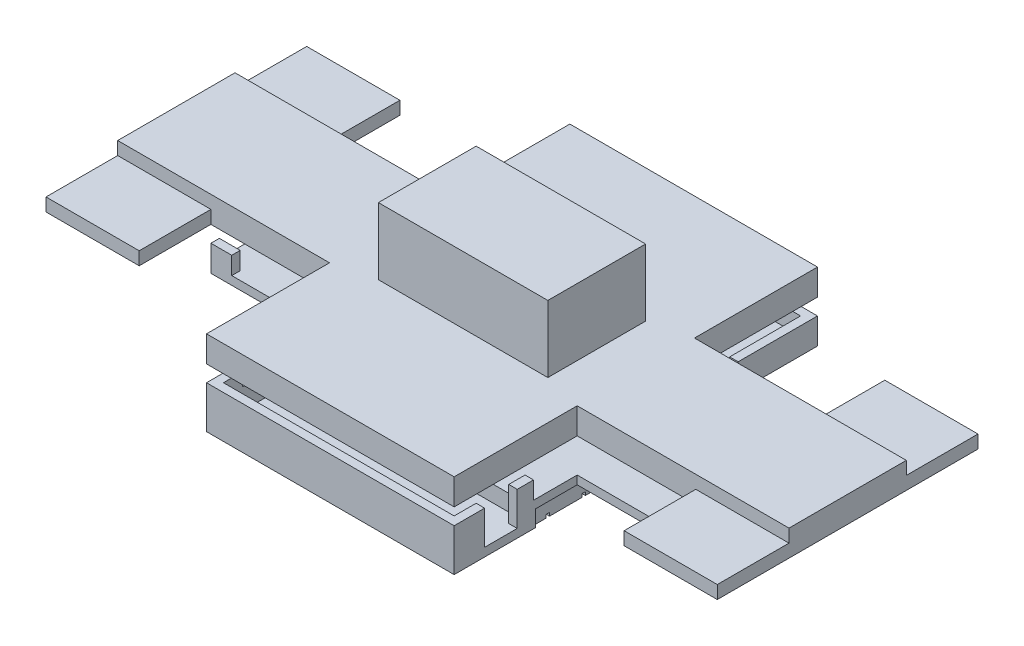
SolidWorks part; units mm, degrees
ref_plane "Front Plane" through (0, 0, 0) normal (0, 0, 1) x (1, 0, 0)
ref_plane "Top Plane" through (0, 0, 0) normal (0, 1, 0) x (1, 0, 0)
ref_plane "Right Plane" through (0, 0, 0) normal (1, 0, 0) x (0, 0, -1)
sketch "Sketch1" plane through (0, 0, 0) normal (0, 1, 0) x (1, 0, 0)
  line L1 (-16.5, 16.5) -> (16.5, 16.5)
  line L2 (-16.5, 16.5) -> (-16.5, -16.5)
  line L3 (-16.5, -16.5) -> (16.5, -16.5)
  line L4 (16.5, 16.5) -> (16.5, -16.5)
  line L5 (-16.5, 16.5) -> (16.5, -16.5) construction
  line L6 (-16.5, -16.5) -> (16.5, 16.5) construction
  point P0 (0, 0)
  dimension "D1" = 33
  dimension "D2" = 33
extrude "Boss-Extrude1" add sketch "Sketch1" along normal blind 13.6
sketch "Sketch2" plane through (0, 13.6, 0) normal (0, 1, 0) x (1, 0, 0)
  line L0 (-10, 3) -> (-10, -3) construction
  line L1 (-3, 3) -> (3, 3)
  line L2 (-3, 3) -> (-3, -3)
  line L3 (-3, -3) -> (3, -3)
  line L4 (3, 3) -> (3, -3)
  line L5 (-3, 3) -> (3, -3) construction
  line L6 (-3, -3) -> (3, 3) construction
  line L7 (-13, 3) -> (-7, 3)
  line L8 (-13, 3) -> (-13, -3)
  line L9 (-13, -3) -> (-7, -3)
  line L10 (-7, 3) -> (-7, -3)
  line L11 (7, 3) -> (13, 3)
  line L12 (7, 3) -> (7, -3)
  line L13 (7, -3) -> (13, -3)
  line L14 (13, 3) -> (13, -3)
  line L15 (10, 3) -> (10, -3) construction
  point P0 (0, 0)
  point P14 (-7, 0)
  point P15 (7, 0)
  point P20 (-10, 0)
  point P21 (10, 0)
  dimension "D1" = 6
  dimension "D2" = 6
  dimension "D3" = 10
  dimension "D4" = 10
extrude "Cut-Extrude1" cut sketch "Sketch2" against normal blind 10
pattern_linear "LPattern1" count 5 spacing 10.3 along (0, 0, 1) of "Cut-Extrude1"
pattern_linear "LPattern2" count 2 spacing 10.3 along (0, 0, -1) of "Cut-Extrude1"
sketch "Sketch3" plane through (0, 0, 0) normal (0, -1, 0) x (1, 0, 0)
  line L0 (-5.5, 16.5) -> (-5.5, -16.5)
  line L1 (-16.5, 16.5) -> (16.5, 16.5) construction
  line L2 (16.5, -16.5) -> (-16.5, -16.5) construction
  line L3 (5.5, 16.5) -> (5.5, -16.5)
  line L4 (-16.5, 5.5) -> (16.5, 5.5)
  line L5 (-16.5, -16.5) -> (-16.5, 16.5) construction
  line L6 (16.5, 16.5) -> (16.5, -16.5) construction
  line L7 (16.5, -5.5) -> (-16.5, -5.5)
  dimension "D1" = 11
  dimension "D2" = 11
  dimension "D3" = 11
  dimension "D4" = 11
extrude "Cut-Extrude-Thin1" cut sketch "Sketch3" against normal blind 1 thin thin type mid plane wall 1
ref_plane "Plane1" through (0, 38.6, 0) normal (0, 1, 0) x (1, 0, 0)
sketch "Sketch4" plane through (0, 38.6, 0) normal (0, 1, 0) x (1, 0, 0)
  line L1 (-103, 18) -> (103, 18)
  line L2 (-103, 18) -> (-103, -18)
  line L3 (-103, -18) -> (103, -18)
  line L4 (103, 18) -> (103, -18)
  line L5 (-103, 18) -> (103, -18) construction
  line L6 (-103, -18) -> (103, 18) construction
  line L7 (-38, 55.75) -> (38, 55.75)
  line L8 (-38, 55.75) -> (-38, -55.75)
  line L9 (-38, -55.75) -> (38, -55.75)
  line L10 (38, 55.75) -> (38, -55.75)
  line L11 (-38, 55.75) -> (38, -55.75) construction
  line L12 (-38, -55.75) -> (38, 55.75) construction
  point P0 (0, 0)
  point P6 (0, 0)
  dimension "D1" = 206
  dimension "D2" = 36
  dimension "D3" = 76
  dimension "D4" = 111.5
extrude "Boss-Extrude2" add sketch "Sketch4" along normal blind 8 separate body contours L10 L7 L8 L1 | L10 L1 L8 L3 | L8 L1 L2 L3 | L10 L3 L8 L9 | L1 L10 L3 L4
shell "Shell1" thickness 2.6
ref_plane "Plane2" through (0, 33.6, 0) normal (0, -1, 0) x (-1, 0, 0)
sketch "Sketch5" plane through (0, 33.6, 0) normal (0, -1, 0) x (-1, 0, 0)
  line L0 (-74.4, 18) -> (-74.4, -18)
  line L3 (-100.4, 15.4) -> (-100.4, -15.4) construction
  line L4 (-38, 18) -> (-103, 18) construction
  line L5 (-38, -18) -> (-103, -18) construction
  line L6 (-74.4, 18) -> (-38, 18)
  line L7 (-38, 18) -> (-38, 55.75)
  line L8 (-38, 55.75) -> (38, 55.75)
  line L9 (38, 55.75) -> (-38, 55.75) construction
  line L10 (-74.4, -18) -> (-38, -18)
  line L11 (-38, -18) -> (-38, -55.75)
  line L12 (-38, -55.75) -> (38, -55.75)
  line L13 (38, -55.75) -> (-38, -55.75) construction
  line L14 (-5, 16.5) -> (5, 16.5) construction
  line L15 (-20, 20) -> (20, 20)
  line L16 (-16.5, 6) -> (-16.5, 16.5) construction
  line L20 (-20, 20) -> (-20, -20)
  line L21 (-20, -20) -> (20, -20)
  line L22 (20, 20) -> (20, -20)
  line L23 (-20, 20) -> (20, -20) construction
  line L24 (-20, -20) -> (20, 20) construction
  line L25 (0, 55.75) -> (0, -55.75) construction
  line L26 (38, -18) -> (38, -55.75)
  line L27 (74.4, -18) -> (38, -18)
  line L28 (74.4, 18) -> (74.4, -18)
  line L29 (74.4, 18) -> (38, 18)
  line L30 (38, 18) -> (38, 55.75)
  point P22 (0, 0)
  dimension "D1" = 26
  dimension "D2" = 3.5
  dimension "D3" = 3.5
extrude "Boss-Extrude3" add sketch "Sketch5" along normal blind 8 separate body
sketch "Sketch6" plane through (0, 25.6, 0) normal (0, -1, 0) x (1, 0, 0)
  line L0 (38, 18) -> (38, 55.75) construction
  line L1 (-38, 55.75) -> (38, 55.75)
  line L2 (-38, 55.75) -> (-38, 30.75)
  line L3 (-38, 30.75) -> (38, 30.75)
  line L4 (38, 55.75) -> (38, 30.75)
  dimension "D1" = 25
extrude "Boss-Extrude4" add sketch "Sketch6" along normal blind 5
shell "Shell2" thickness 2.6
sketch "Sketch7" plane through (0, 38.6, 0) normal (0, -1, 0) x (1, 0, 0)
  line L0 (74.4, 15.4) -> (100.4, 15.4)
  line L1 (35.4, 15.4) -> (100.4, 15.4) construction
  line L2 (35.4, 15.4) -> (100.4, 15.4) construction
  line L3 (100.4, 15.4) -> (100.4, -15.4)
  line L4 (100.4, -15.4) -> (74.4, -15.4)
  line L5 (74.4, -18) -> (74.4, 18) construction
  line L6 (35.4, -15.4) -> (100.4, -15.4) construction
  line L7 (74.4, -15.4) -> (74.4, -40)
  line L8 (74.4, -40) -> (103, -40)
  line L9 (103, -40) -> (103, 40)
  line L10 (103, 40) -> (74.4, 40)
  line L11 (74.4, 40) -> (74.4, 15.4)
  line L12 (38, 18) -> (103, 18) construction
  point P14 (103, 0)
  dimension "D1" = 22
  dimension "D2" = 28.6
extrude "Boss-Extrude5" add sketch "Sketch7" against normal blind 4
mirror "Mirror1" about plane through (0, 0, 0) normal (1, 0, 0) of "Boss-Extrude5"
sketch "Sketch8" plane through (-38, 0, 0) normal (-1, 0, 0) x (0, 0, 1)
  line L0 (43.25, 20.6) -> (43.25, 33.6) construction
  line L1 (55.75, 20.6) -> (30.75, 20.6) construction
  line L2 (55.75, 33.6) -> (18, 33.6) construction
  line L4 (39.25, 37.6) -> (47.25, 37.6)
  line L5 (39.25, 37.6) -> (39.25, 29.6)
  line L6 (39.25, 29.6) -> (47.25, 29.6)
  line L7 (47.25, 37.6) -> (47.25, 29.6)
  line L8 (39.25, 37.6) -> (47.25, 29.6) construction
  line L9 (39.25, 29.6) -> (47.25, 37.6) construction
  dimension "D1" = 4
  dimension "D2" = 8
extrude "Cut-Extrude2" cut sketch "Sketch8" against normal up to next (2.6 mm away)
sketch "Sketch9" plane through (0, 46.6, 0) normal (0, 1, 0) x (1, 0, 0)
  line L1 (-26, 15) -> (26, 15)
  line L2 (-26, 15) -> (-26, -15)
  line L3 (-26, -15) -> (26, -15)
  line L4 (26, 15) -> (26, -15)
  line L5 (-26, 15) -> (26, -15) construction
  line L6 (-26, -15) -> (26, 15) construction
  point P0 (0, 0)
  dimension "D1" = 52
  dimension "D2" = 30
extrude "Boss-Extrude6" add sketch "Sketch9" along normal blind 20.5
sketch "Sketch10" plane through (-26, 0, 0) normal (-1, 0, 0) x (0, 0, 1)
  line L0 (0, 67.1) -> (0, 46.6) construction
  line L1 (-15, 67.1) -> (15, 67.1) construction
  line L2 (-18, 46.6) -> (18, 46.6) construction
  line L8 (-15, 67.1) -> (-15, 46.6) construction
  line L9 (-12, 64.1) -> (12, 64.1)
  line L10 (-12, 64.1) -> (-12, 46.6)
  line L11 (-12, 46.6) -> (12, 46.6)
  line L12 (12, 64.1) -> (12, 46.6)
  line L13 (15, 67.1) -> (15, 46.6) construction
  line L14 (-15, 46.6) -> (15, 46.6) construction
  point P6 (0, 56.85)
  dimension "D1" = 3
  dimension "D2" = 3
  dimension "D3" = 3
extrude "Cut-Extrude3" cut sketch "Sketch10" against normal offset from surface (49 mm away) 3 up to face at (26, 56.85, 0)
sketch "Sketch11" plane through (38, 0, 0) normal (1, 0, 0) x (0, 0, -1)
  line L1 (-15.4, 33.6) -> (-31.4, 33.6)
  line L2 (-15.4, 33.6) -> (-15.4, 28.2)
  line L3 (-15.4, 28.2) -> (-31.4, 28.2)
  line L4 (-31.4, 33.6) -> (-31.4, 28.2)
  line L5 (-15.4, 28.2) -> (15.4, 28.2) construction
  point P7 (-23.4, 28.2)
  dimension "D1" = 16
extrude "Cut-Extrude4" cut sketch "Sketch11" against normal up to next (2.6 mm away)
sketch "Sketch13" plane through (0, 0, 18) normal (0, 0, 1) x (1, 0, 0)
  line L0 (-35.4, 28.2) -> (35.4, 28.2) construction
  line L1 (38, 33.6) -> (68, 33.6)
  line L2 (38, 33.6) -> (38, 28.2)
  line L3 (38, 28.2) -> (68, 28.2)
  line L4 (68, 33.6) -> (68, 28.2)
  dimension "D1" = 30
extrude "Cut-Extrude5" cut sketch "Sketch13" against normal up to next (2.6 mm away)
mirror "Mirror2" about plane through (0, 0, 0) normal (0, 0, 1) of "Cut-Extrude4", "Cut-Extrude5"
mirror "Mirror3" about plane through (0, 0, 0) normal (1, 0, 0) of "Mirror2", "Cut-Extrude4", "Cut-Extrude5"
sketch "Sketch14" plane through (38, 0, 0) normal (1, 0, 0) x (0, 0, -1)
  line L0 (-31.4, 33.6) -> (-55.75, 33.6) construction
  line L1 (-36.4, 33.6) -> (-46.4, 33.6)
  line L2 (-36.4, 33.6) -> (-36.4, 23.2)
  line L3 (-36.4, 23.2) -> (-46.4, 23.2)
  line L4 (-46.4, 33.6) -> (-46.4, 23.2)
  line L5 (-31.4, 33.6) -> (-31.4, 28.2) construction
  line L6 (-53.15, 23.2) -> (-33.35, 23.2) construction
  dimension "D1" = 5
  dimension "D2" = 10
extrude "Cut-Extrude6" cut sketch "Sketch14" against normal up to next (2.6 mm away)
sketch "Sketch15" plane through (74.4, 0, 0) normal (1, 0, 0) x (0, 0, -1)
  line L0 (18, 33.6) -> (-18, 33.6) construction
  line L1 (-15.4, 33.6) -> (15.4, 33.6)
  line L2 (-15.4, 33.6) -> (-15.4, 28.2)
  line L3 (-15.4, 28.2) -> (15.4, 28.2)
  line L4 (15.4, 33.6) -> (15.4, 28.2)
extrude "Cut-Extrude7" cut sketch "Sketch15" against normal through all both and the other way through all
equation "\"D2@Sketch2\"=\"D1@Sketch2\""
equation "\"D4@Sketch2\"=\"D3@Sketch2\""
equation "\"D2@Sketch3\"=\"D1@Sketch3\""
equation "\"D3@Sketch3\"=\"D1@Sketch3\""
equation "\"D4@Sketch3\"=\"D1@Sketch3\""
